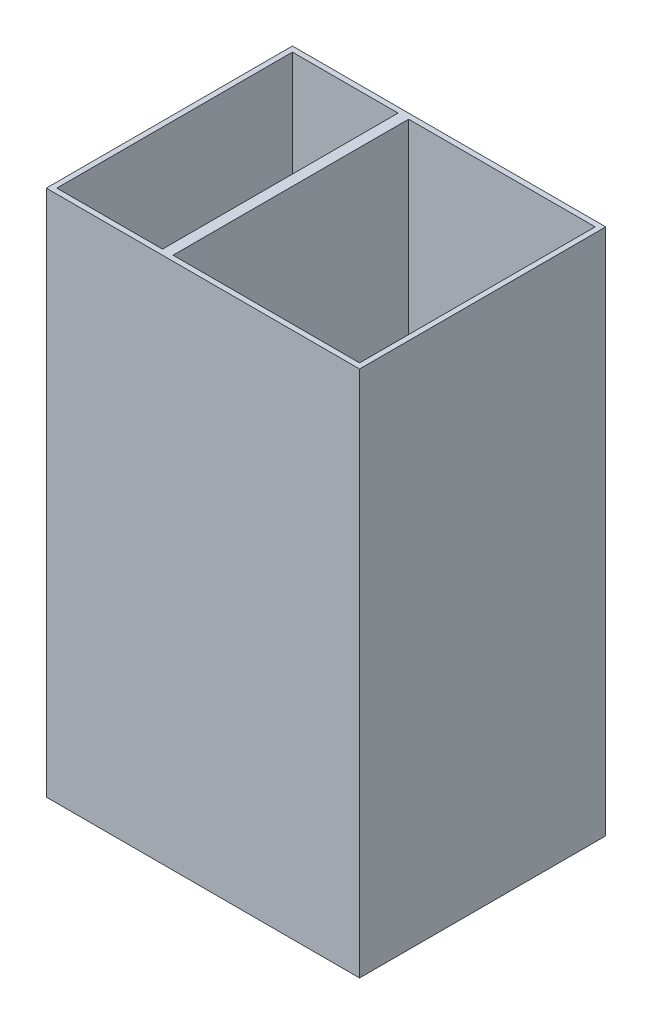
SolidWorks part; units mm, degrees
material "Faia"
ref_plane "Plano frontal" through (0, 0, 0) normal (0, 0, 1) x (1, 0, 0)
ref_plane "Plano superior" through (0, 0, 0) normal (0, 1, 0) x (1, 0, 0)
ref_plane "Plano direito" through (0, 0, 0) normal (1, 0, 0) x (0, 0, -1)
ref_plane "Plano2" through (35.065, 0, 0) normal (1, 0, 0) x (0, 0, -1)
sketch "Esboço1" plane through (0, 0, 0) normal (0, 1, 0) x (1, 0, 0)
  line L0 (0, 40.7379) -> (0, -51.835) construction
  line L1 (-44.55, -35) -> (44.55, -35)
  line L2 (-44.55, -35) -> (-44.55, 35)
  line L3 (-44.55, 35) -> (44.55, 35)
  line L4 (44.55, -35) -> (44.55, 35)
  line L5 (-44.55, -35) -> (44.55, 35) construction
  line L6 (-44.55, 35) -> (44.55, -35) construction
  line L7 (-10, 33.5) -> (-10, -33.5)
  line L8 (-43.05, -33.5) -> (-13, -33.5)
  line L9 (-43.05, -33.5) -> (-43.05, 33.5)
  line L10 (-43.05, 33.5) -> (-13, 33.5)
  line L11 (43.05, -33.5) -> (43.05, 33.5)
  line L12 (-43.05, -33.5) -> (43.05, 33.5) construction
  line L13 (-43.05, 33.5) -> (43.05, -33.5) construction
  line L14 (-13, 33.5) -> (-13, -33.5)
  line L15 (-13, 35) -> (-13, -35) construction
  line L16 (-10, 35) -> (-10, -35) construction
  line L17 (-10, 33.5) -> (43.05, 33.5)
  line L18 (-10, -33.5) -> (43.05, -33.5)
  point P0 (0, 0)
  point P8 (0, 0)
  dimension "D1" = 70
  dimension "D2" = 89.1
  dimension "D3" = 67
  dimension "D4" = 86.1
  dimension "D5" = 10
  dimension "D6" = 3
extrude "Ressalto-extrusão1" add sketch "Esboço1" along normal blind 150
ref_plane "Plano3" through (0, 75, 0) normal (0, -1, 0) x (-1, 0, 0)
sketch "Esboço3" plane through (-10, 0, 0) normal (1, 0, 0) x (0, 0, -1)
  line L0 (0, -29.3971) -> (0, 77.9106) construction
  line L1 (67.6018, 75.0346) -> (15.5, 75.0346) construction
  line L2 (17.5, 75.0346) -> (15.5, 75.0346) construction
  line L5 (0, 78.5096) -> (0, 178.0004) construction
  line L6 (-15.5, 75.0346) -> (-20.3761, 75.0346) construction
  line L7 (-15.5, 75.0346) -> (-17.5, 75.0346) construction
  circle A3 centre (17.5, 75.0346) radius 2
  circle A4 centre (-17.5, 75.0346) radius 2
  circle A5 centre (0, 83.0346) radius 4.525
  point P9 (0, 75.0346)
  dimension "D1" = 8
  dimension "D2" = 9.05
extrude "Corte-extrusão1" cut sketch "Esboço3" against normal blind 3
